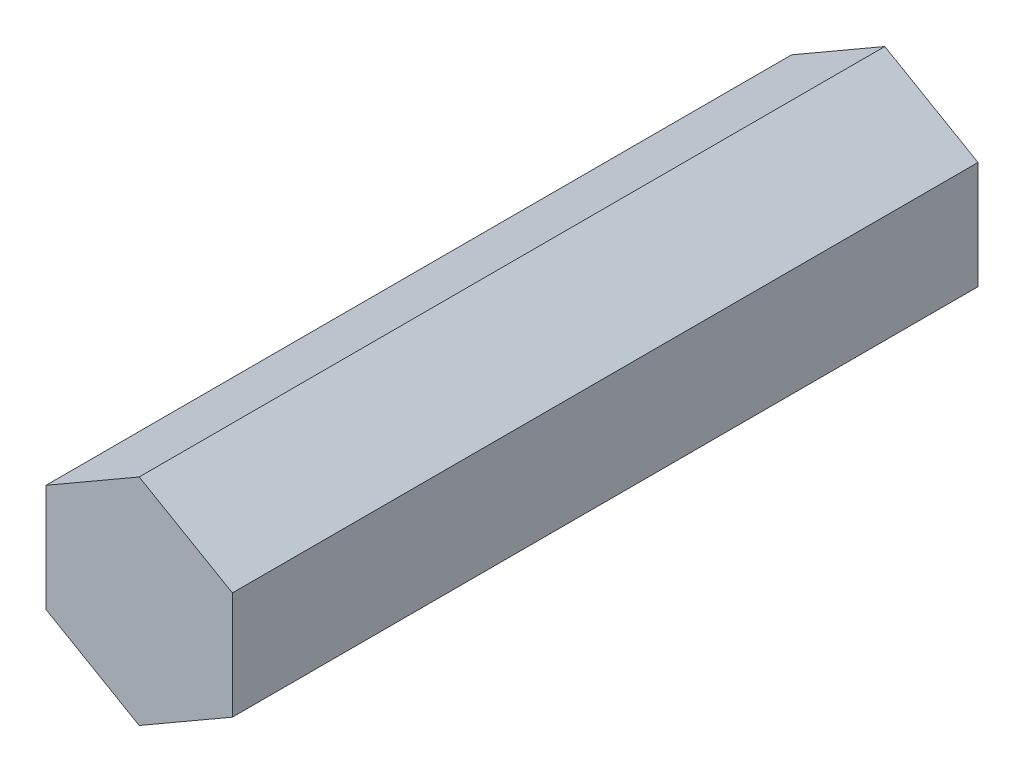
SolidWorks part; units mm, degrees
ref_plane "Front Plane" through (0, 0, 0) normal (0, 0, 1) x (1, 0, 0)
ref_plane "Top Plane" through (0, 0, 0) normal (0, 1, 0) x (1, 0, 0)
ref_plane "Right Plane" through (0, 0, 0) normal (1, 0, 0) x (0, 0, -1)
sketch "Esboço2" plane through (0, 0, 0) normal (0, 0, 1) x (1, 0, 0)
  line L1 (15, 8.6603) -> (0, 17.3205)
  line L2 (0, 17.3205) -> (-15, 8.6603)
  line L3 (-15, 8.6603) -> (-15, -8.6603)
  line L4 (-15, -8.6603) -> (0, -17.3205)
  line L5 (0, -17.3205) -> (15, -8.6603)
  line L6 (15, -8.6603) -> (15, 8.6603)
  circle A1 centre (0, 0) radius 15 construction
  dimension "D1" = 30
extrude "Ressalto-extrusão1" add sketch "Esboço2" along normal blind 120
sketch "Esboço1" plane through (0, 0, 0) normal (0, 0, 1) x (1, 0, 0)
  line L1 (9, 5.1962) -> (0, 10.3923)
  line L2 (0, 10.3923) -> (-9, 5.1962)
  line L3 (-9, 5.1962) -> (-9, -5.1962)
  line L4 (-9, -5.1962) -> (0, -10.3923)
  line L5 (0, -10.3923) -> (9, -5.1962)
  line L6 (9, -5.1962) -> (9, 5.1962)
  circle A0 centre (0, 0) radius 9 construction
  dimension "D1" = 18
extrude "Corte-extrusão1" cut sketch "Esboço1" along normal blind 40
